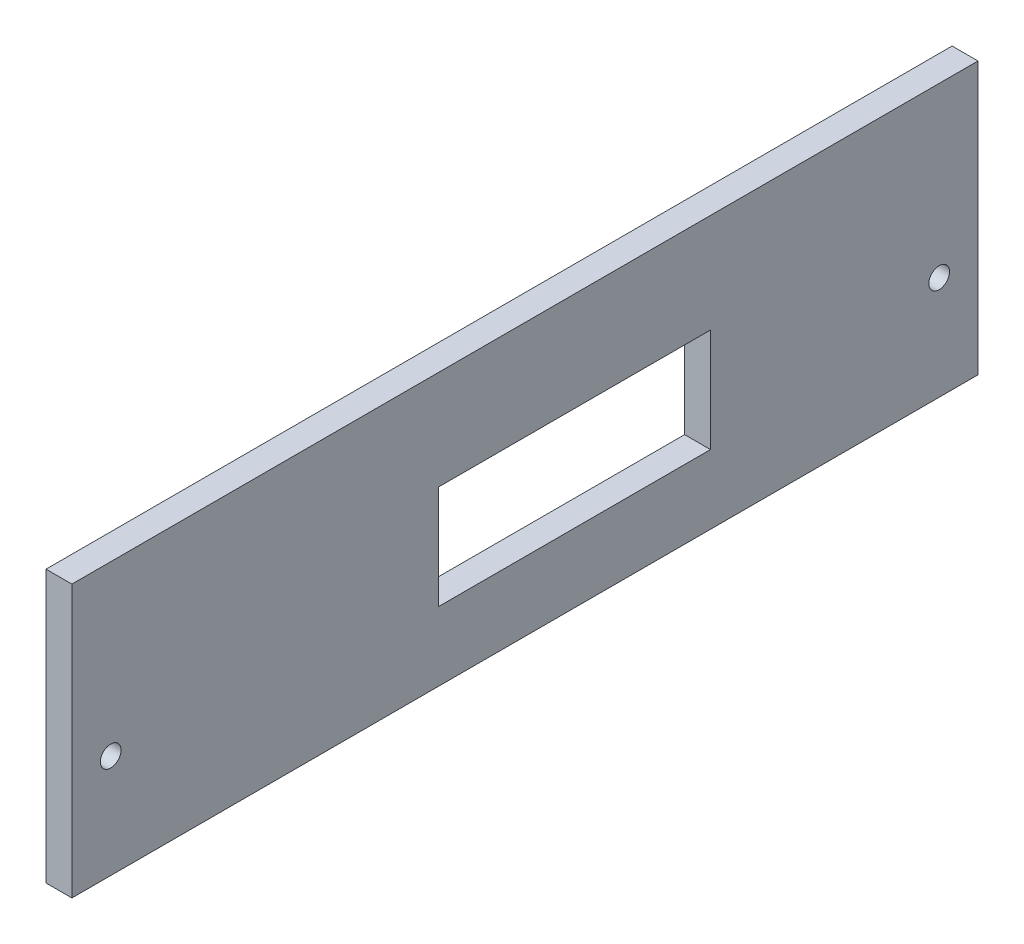
SolidWorks part; units mm, degrees
ref_plane "Front Plane" through (0, 0, 0) normal (0, 0, 1) x (1, 0, 0)
ref_plane "Top Plane" through (0, 0, 0) normal (0, 1, 0) x (1, 0, 0)
ref_plane "Right Plane" through (0, 0, 0) normal (1, 0, 0) x (0, 0, -1)
sketch "Sketch8" plane through (0, 0, 0) normal (-1, 0, 0) x (0, 0, 1)
  line L0 (-51.75, 14.5) -> (0.75, 14.5)
  line L1 (0.75, -1.25) -> (0.75, 14.5)
  line L2 (0.75, -1.25) -> (-51.75, -1.25)
  line L3 (-51.75, 14.5) -> (-51.75, -1.25)
  line L4 (-36.25, 8.75) -> (-36.25, 2.75)
  line L5 (-36.25, 8.75) -> (-20.5, 8.75)
  line L6 (-20.5, 8.75) -> (-20.5, 2.75)
  line L7 (-20.5, 2.75) -> (-36.25, 2.75)
  circle A0 centre (-49.5, 4.75) radius 0.6
  circle A1 centre (-1.5, 4.75) radius 0.6
  dimension "D1" = 6
  dimension "D2" = 6
  dimension "D3" = 15.75
  dimension "D4" = 48
  dimension "D5" = 15.5
  dimension "D6" = 15.75
  dimension "D7" = 4
  dimension "D8" = 6
extrude "Boss-Extrude13" add sketch "Sketch8" along normal blind 1.5
